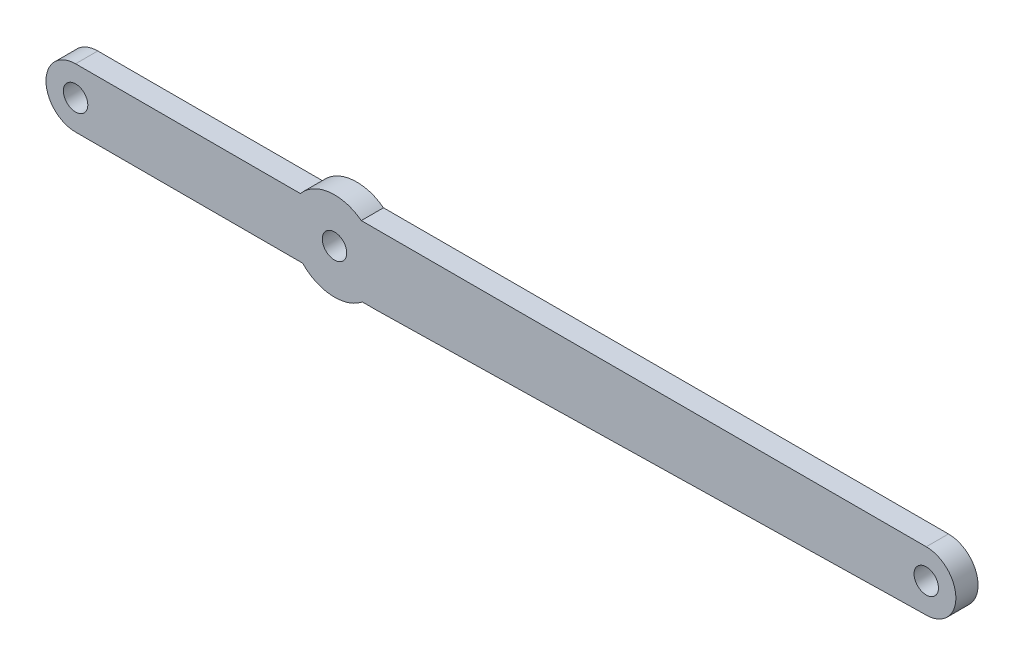
SolidWorks part; units mm, degrees
ref_plane "前视基准面" through (0, 0, 0) normal (0, 0, 1) x (1, 0, 0)
ref_plane "上视基准面" through (0, 0, 0) normal (0, 1, 0) x (1, 0, 0)
ref_plane "右视基准面" through (0, 0, 0) normal (1, 0, 0) x (0, 0, -1)
ref_plane "基准面4" through (0, 0, 3) normal (0, 0, 1) x (1, 0, 0)
sketch "草图1" plane through (0, 0, 3) normal (0, 0, 1) x (1, 0, 0)
  line L0 (-60.8325, 7.5141) -> (-91.2187, 7.5141)
  line L1 (-91.2187, -0.4859) -> (-60.5316, -0.4859)
  line L2 (-52.4516, -0.9904) -> (-50.421, -0.9904)
  line L3 (-50.421, -0.9904) -> (23.8166, 0.4678)
  line L4 (23.778, 8.4676) -> (-52.5964, 8.4676)
  line L5 (23.8166, 0.4678) -> (23.8566, 0.4686)
  arc A0 (-52.5964, 8.4676) -> (-60.8325, 7.5141) centre (-56.2156, 3.6821) ccw
  arc A1 (-91.2187, 7.5141) -> (-91.2187, -0.4859) centre (-91.2187, 3.5141) ccw
  arc A2 (-60.5316, -0.4859) -> (-52.4516, -0.9904) centre (-56.2156, 3.6821) ccw
  arc A3 (23.8566, 0.4686) -> (23.778, 8.4676) centre (23.778, 4.4677) ccw
extrude "凸台-拉伸1" add sketch "草图1" against normal blind 3
sketch "草图2" plane through (0, 0, 3) normal (0, 0, 1) x (1, 0, 0)
  circle A0 centre (23.778, 4.4676) radius 1.35
extrude "切除-拉伸1" cut sketch "草图2" against normal blind 2.4444
sketch "草图3" plane through (0, 0, 0) normal (0, 0, -1) x (-1, 0, 0)
  circle A0 centre (-23.778, 4.4678) radius 1.65
  circle A1 centre (56.2156, 3.6821) radius 1.65
  circle A2 centre (91.2187, 3.5141) radius 1.65
  dimension "D1" = 3.3
  dimension "D2" = 3.3
  dimension "D3" = 3.3
extrude "切除-拉伸3" cut sketch "草图3" against normal through all contours A0 | A1 | A2
sketch "草图4" plane through (0, 0, 0) normal (0, 0, -1) x (-1, 0, 0)
  text T0 "5"
extrude "切除-拉伸4" cut sketch "草图4" against normal blind 1
